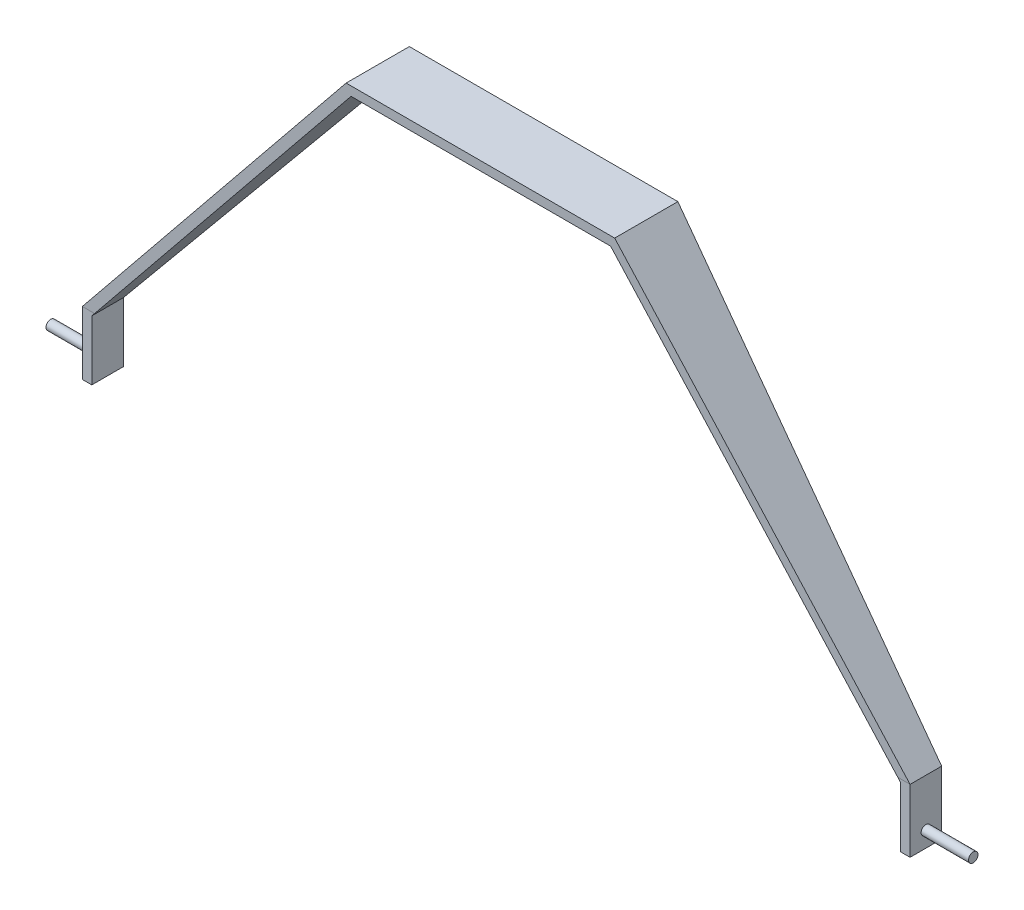
SolidWorks part; units mm, degrees
ref_plane "Front Plane" through (0, 0, 0) normal (0, 0, 1) x (1, 0, 0)
ref_plane "Top Plane" through (0, 0, 0) normal (0, 1, 0) x (1, 0, 0)
ref_plane "Right Plane" through (0, 0, 0) normal (1, 0, 0) x (0, 0, -1)
sketch "Sketch5" plane through (0, 0, 0) normal (0, 0, 1) x (1, 0, 0)
  line L0 (-42.5, 0) -> (42.5, 0)
  line L1 (42.5, 0) -> (131, -108)
  line L2 (131, -108) -> (131, -128)
  line L3 (131, -128) -> (128, -128)
  line L4 (128, -128) -> (128, -109.0722)
  line L5 (128, -109.0722) -> (41.0798, -3)
  line L6 (41.0798, -3) -> (-41.0798, -3)
  line L7 (0, -3) -> (0, 0)
  line L8 (0, 0) -> (0, -158.8716) construction
  line L9 (-128, -109.0722) -> (-41.0798, -3)
  line L10 (-128, -128) -> (-128, -109.0722)
  line L11 (-131, -128) -> (-128, -128)
  line L12 (-131, -108) -> (-131, -128)
  line L13 (-42.5, 0) -> (-131, -108)
  point P4 (131, -118)
  dimension "D1" = 3
  dimension "D2" = 3
  dimension "D3" = 3
  dimension "D4" = 125
  dimension "D5" = 105
  dimension "D6" = 42.5
  dimension "D7" = 128
extrude "Boss-Extrude1" add sketch "Sketch5" along normal blind 20 contours L0 L13 L12 L11 L10 L9 L6 L7 | L7 L6 L5 L4 L3 L2 L1 L0
sketch "Sketch6" plane through (131, 0, 0) normal (1, 0, 0) x (0, 0, -1)
  line L0 (-15, -128) -> (-15, -108)
  line L1 (-20, -128) -> (0, -128) construction
  line L2 (-20, -108) -> (0, -108) construction
  line L3 (-15, -108) -> (-20, 0)
  line L4 (-20, 0) -> (0, 0)
  line L5 (0, 0) -> (-5, -108)
  line L6 (-5, -108) -> (-5, -128)
  line L7 (-5, -128) -> (-15, -128)
  line L8 (-20, -108) -> (-20, -128) construction
  line L9 (0, -108) -> (0, -128) construction
  line L11 (0, -128) -> (-20, -128)
  line L12 (0, -128) -> (0, 0)
  line L13 (0, 0) -> (-20, 0)
  line L14 (-20, -128) -> (-20, 0)
  line M7 (0, -128) -> (0, -108)
  line M8 (0, -108) -> (-20, -108)
  line M9 (-20, -108) -> (-20, -128)
  line M10 (-20, -128) -> (0, -128)
  dimension "D1" = 5
  dimension "D2" = 5
extrude "Cut-Extrude1" cut sketch "Sketch6" against normal through all contours L0 M10 M8 M9 | L14 L3 M8 | L12 L5 M8 | L6 M8 M10 M7
sketch "Sketch7" plane through (131, 0, 0) normal (1, 0, 0) x (0, 0, -1)
  line L0 (-15, -128) -> (-5, -128) construction
  line L1 (-5, -108) -> (-5, -128) construction
  circle A0 centre (-10, -123) radius 1.5
  dimension "D1" = 3
  dimension "D2" = 5
  dimension "D3" = 5
extrude "Boss-Extrude2" add sketch "Sketch7" along normal blind 15
sketch "Sketch8" plane through (-131, 0, 0) normal (-1, 0, 0) x (0, 0, 1)
  line L0 (15, -128) -> (5, -128) construction
  line L1 (15, -128) -> (15, -108) construction
  circle A0 centre (10, -123) radius 1.5
  dimension "D1" = 3
  dimension "D2" = 5
  dimension "D3" = 5
extrude "Boss-Extrude3" add sketch "Sketch8" along normal blind 15
